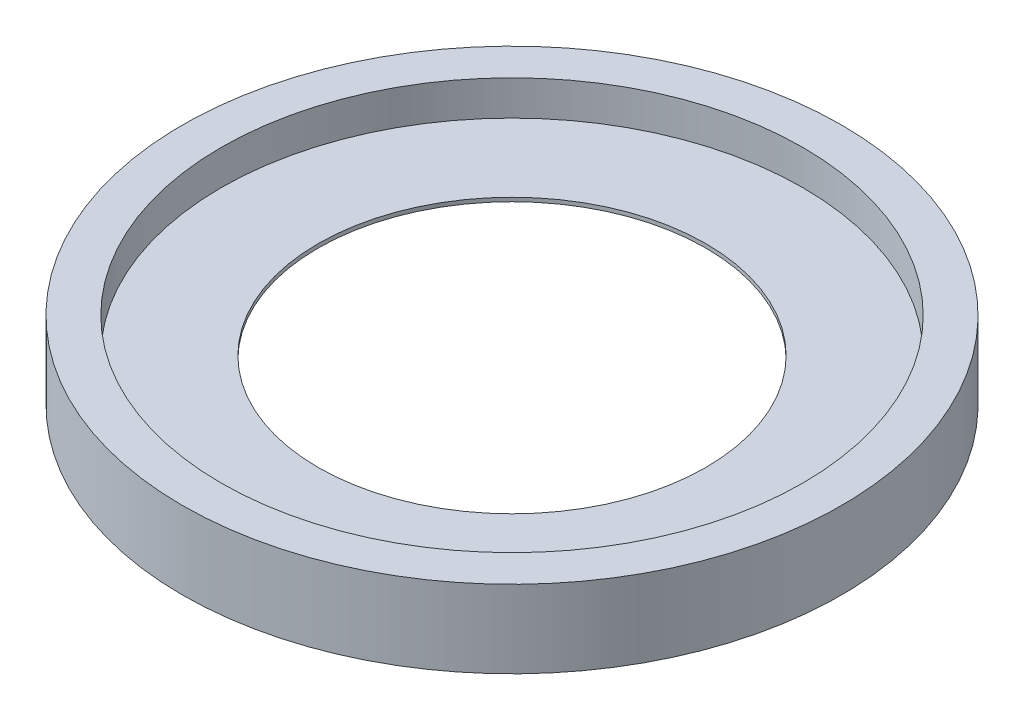
SolidWorks part; units mm, degrees
material "NBR"
ref_plane "Front Plane" through (0, 0, 0) normal (0, 0, 1) x (1, 0, 0)
ref_plane "Top Plane" through (0, 0, 0) normal (0, 1, 0) x (1, 0, 0)
ref_plane "Right Plane" through (0, 0, 0) normal (1, 0, 0) x (0, 0, -1)
sketch "Sketch1" plane through (0, 0, 0) normal (0, 1, 0) x (1, 0, 0)
  circle A0 centre (0, 0) radius 8.5
  circle A1 centre (0, 0) radius 7.5
  dimension "D1" = 17
  dimension "D2" = 15
extrude "Boss-Extrude1" add sketch "Sketch1" along normal blind 2
sketch "Sketch2" plane through (0, 2, 0) normal (0, 1, 0) x (1, 0, 0)
  circle A0 centre (0, 0) radius 7.5
  circle A1 centre (0, 0) radius 5
  dimension "D1" = 10
extrude "Boss-Extrude2" add sketch "Sketch2" along normal blind 0.1 from offset 1
